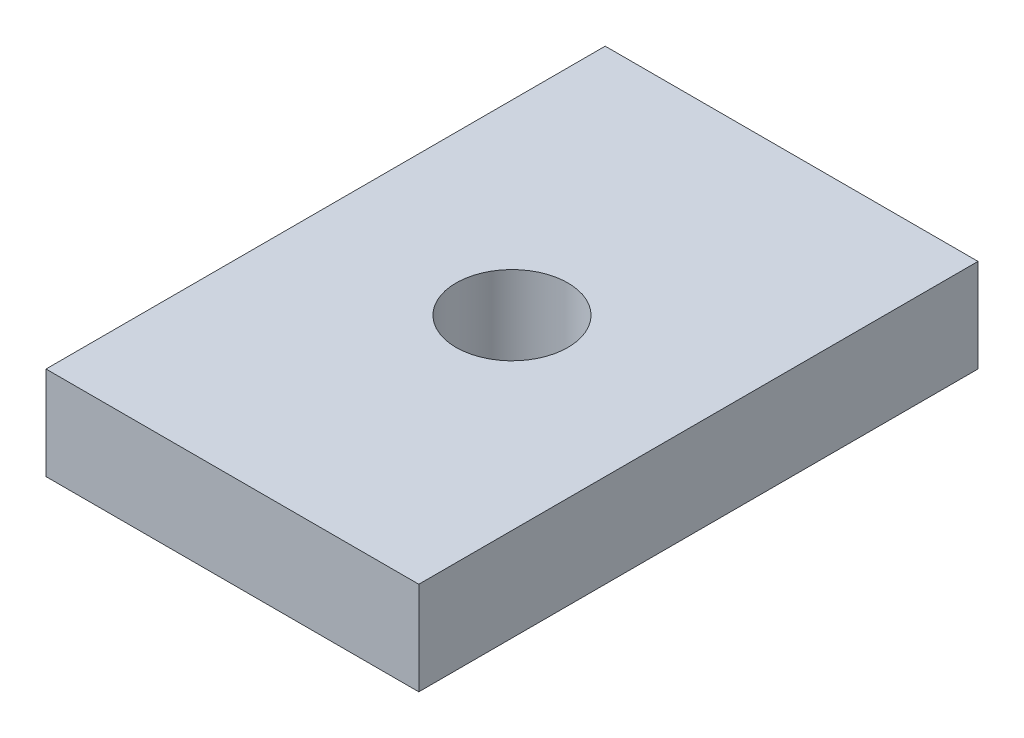
SolidWorks part; units mm, degrees
ref_plane "Front Plane" through (0, 0, 0) normal (0, 0, 1) x (1, 0, 0)
ref_plane "Top Plane" through (0, 0, 0) normal (0, 1, 0) x (1, 0, 0)
ref_plane "Right Plane" through (0, 0, 0) normal (1, 0, 0) x (0, 0, -1)
sketch "Sketch1" plane through (0, 0, 0) normal (0, 1, 0) x (1, 0, 0)
  line L1 (-10, -15) -> (10, -15)
  line L2 (-10, -15) -> (-10, 15)
  line L3 (-10, 15) -> (10, 15)
  line L4 (10, -15) -> (10, 15)
  line L5 (-10, -15) -> (10, 15) construction
  line L6 (-10, 15) -> (10, -15) construction
  circle A0 centre (0, 0) radius 3
  point P0 (0, 0)
  dimension "D3" = 6
  dimension "D1" = 20
  dimension "D2" = 30
extrude "Boss-Extrude1" add sketch "Sketch1" along normal blind 5
